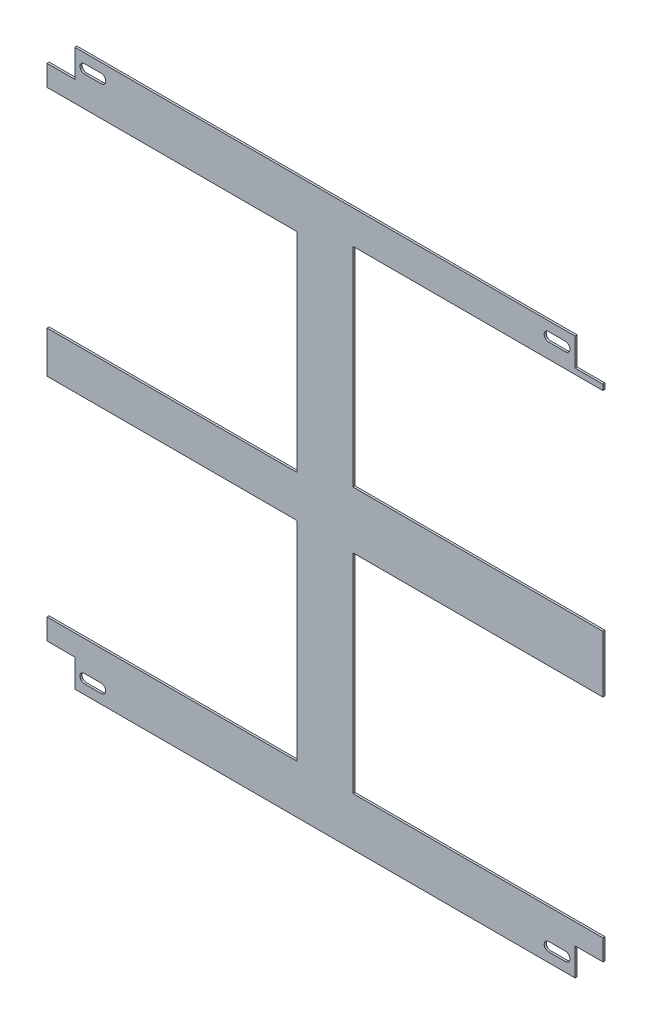
SolidWorks part; units mm, degrees
ref_plane "前视基准面" through (0, 0, 0) normal (0, 0, 1) x (1, 0, 0)
ref_plane "上视基准面" through (0, 0, 0) normal (0, 1, 0) x (1, 0, 0)
ref_plane "右视基准面" through (0, 0, 0) normal (1, 0, 0) x (0, 0, -1)
sketch "草图1" plane through (0, 0, 0) normal (0, 0, 1) x (1, 0, 0)
  line L0 (-10, 366) -> (-160, 366)
  line L1 (-160, 366) -> (-160, 216)
  line L2 (-160, 216) -> (-10, 216)
  line L4 (-10, 175) -> (-160, 175)
  line L5 (-160, 175) -> (-160, 25)
  line L12 (0, -10) -> (0, 10)
  line L13 (0, 10) -> (20, 10)
  line L14 (20, 10) -> (20, 370)
  line L15 (20, 370) -> (0, 370)
  line L16 (0, 370) -> (0, 390)
  line L17 (0, 390) -> (-360, 390)
  line L18 (-360, 390) -> (-360, 370)
  line L19 (-360, 370) -> (-380, 370)
  line L20 (-380, 370) -> (-380, 10)
  line L21 (-380, 10) -> (-360, 10)
  line L22 (-360, 10) -> (-360, -10)
  line L23 (-360, -10) -> (0, -10)
  line L24 (0, -10) -> (0, 10)
  line L25 (0, 10) -> (20, 10)
  line L26 (20, 10) -> (20, 25)
  line L27 (20, 370) -> (0, 370)
  line L28 (0, 370) -> (0, 390)
  line L29 (0, 390) -> (-360, 390)
  line L30 (-360, 390) -> (-360, 370)
  line L31 (-360, 370) -> (-380, 370)
  line L32 (-380, 370) -> (-380, 355)
  line L33 (-380, 10) -> (-360, 10)
  line L34 (-360, 10) -> (-360, -10)
  line L35 (-360, -10) -> (0, -10)
  line L36 (-160, 25) -> (-10, 25)
  line L38 (-350, 205) -> (-200, 205)
  line L39 (-200, 205) -> (-200, 355)
  line L40 (-200, 355) -> (-350, 355)
  line L66 (-350, 25) -> (-200, 25)
  line L67 (-200, 25) -> (-200, 175)
  line L68 (-200, 175) -> (-350, 175)
  line L70 (-380, 355) -> (-350, 355)
  line L71 (-353, -3.25) -> (-341, -3.25)
  line L72 (-380, 205) -> (-350, 205)
  line L73 (-380, 175) -> (-350, 175)
  line L74 (-380, 25) -> (-350, 25)
  line L75 (-10, 366) -> (20, 366)
  line L76 (-10, 216) -> (20, 216)
  line L77 (-10, 175) -> (20, 175)
  line L78 (-10, 25) -> (20, 25)
  line L79 (-380, 25) -> (-380, 10)
  line L80 (20, 175) -> (20, 216)
  line L81 (20, 366) -> (20, 370)
  line L82 (-380, 205) -> (-380, 175)
  line L83 (-353, 3.25) -> (-341, 3.25)
  line L84 (-19, -3.25) -> (-7, -3.25)
  line L85 (-19, 3.25) -> (-7, 3.25)
  line L86 (-380, 190) -> (-268.4088, 190) construction
  line L87 (-19, 376.75) -> (-7, 376.75)
  line L88 (-19, 383.25) -> (-7, 383.25)
  line L89 (-353, 376.75) -> (-341, 376.75)
  line L90 (-353, 383.25) -> (-341, 383.25)
  arc A0 (-353, 3.25) -> (-353, -3.25) centre (-353, 0) ccw construction
  arc A1 (-353, 3.25) -> (-353, -3.25) centre (-353, 0) ccw
  arc A2 (-341, -3.25) -> (-341, 3.25) centre (-341, 0) ccw construction
  arc A3 (-341, -3.25) -> (-341, 3.25) centre (-341, 0) ccw
  arc A4 (-19, 3.25) -> (-19, -3.25) centre (-19, 0) ccw construction
  arc A5 (-19, 3.25) -> (-19, -3.25) centre (-19, 0) ccw
  arc A6 (-7, -3.25) -> (-7, 3.25) centre (-7, 0) ccw construction
  arc A7 (-7, -3.25) -> (-7, 3.25) centre (-7, 0) ccw
  arc A8 (-7, 383.25) -> (-7, 376.75) centre (-7, 380) cw
  arc A9 (-19, 376.75) -> (-19, 383.25) centre (-19, 380) cw
  arc A10 (-341, 383.25) -> (-341, 376.75) centre (-341, 380) cw
  arc A11 (-353, 376.75) -> (-353, 383.25) centre (-353, 380) cw
  dimension "D1" = 0
extrude "凸台-拉伸1" add sketch "草图1" along normal blind 1.5
